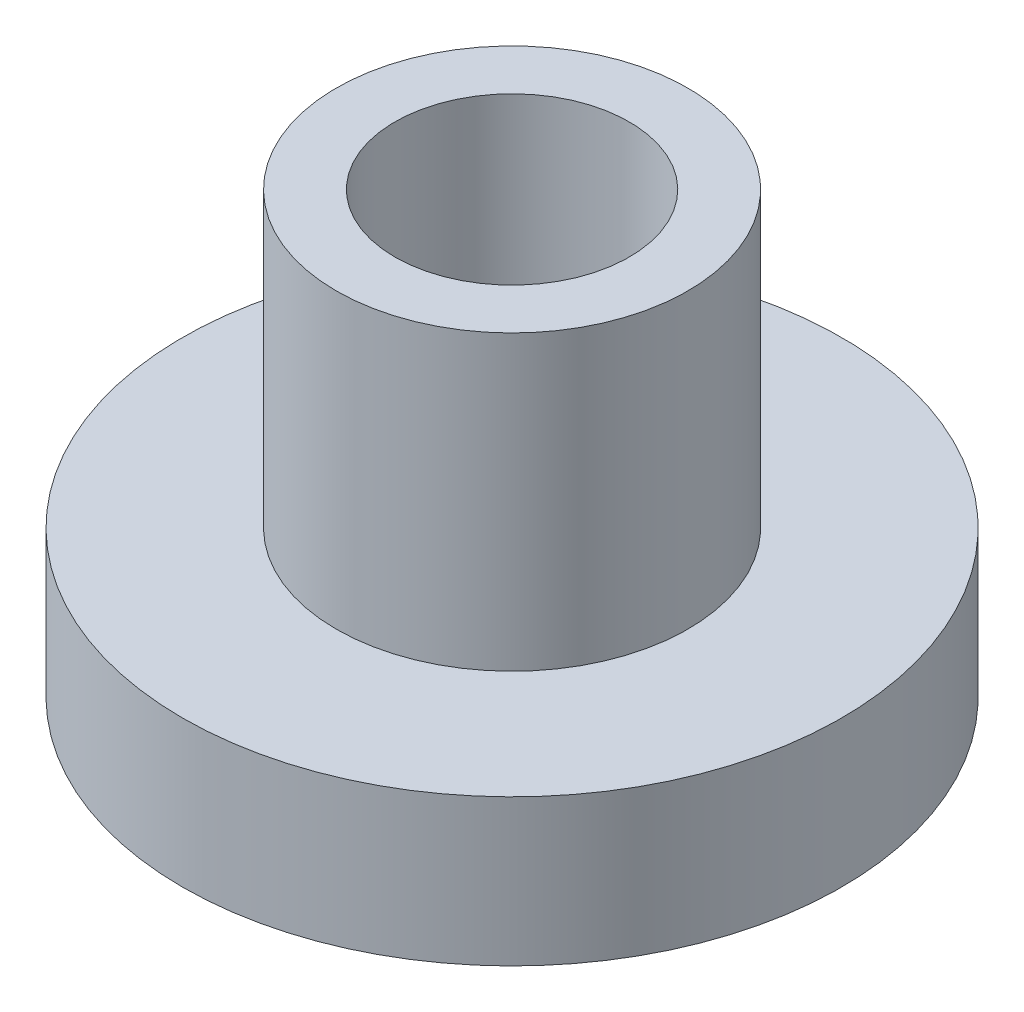
SolidWorks part; units mm, degrees
material "PET"
ref_plane "Plan de face" through (0, 0, 0) normal (0, 0, 1) x (1, 0, 0)
ref_plane "Plan de dessus" through (0, 0, 0) normal (0, 1, 0) x (1, 0, 0)
ref_plane "Plan de droite" through (0, 0, 0) normal (1, 0, 0) x (0, 0, -1)
sketch "Esquisse1" plane through (0, 0, 0) normal (1, 0, 0) x (0, 0, -1)
  line L0 (0, 6.8481) -> (0, -1.1972) construction
  line L1 (-1.6, 0) -> (-1.6, 6)
  line L2 (-1.6, 6) -> (-2.4, 6)
  line L3 (-2.4, 6) -> (-2.4, 2)
  line L4 (-2.4, 2) -> (-4.5, 2)
  line L5 (-4.5, 2) -> (-4.5, 0)
  line L6 (-4.5, 0) -> (-1.6, 0)
  dimension "D1" = 3.2
  dimension "D2" = 4.8
  dimension "D3" = 9
  dimension "D4" = 2
  dimension "D5" = 6
revolve "Révolution1" add sketch "Esquisse1" angle 360 about L0
